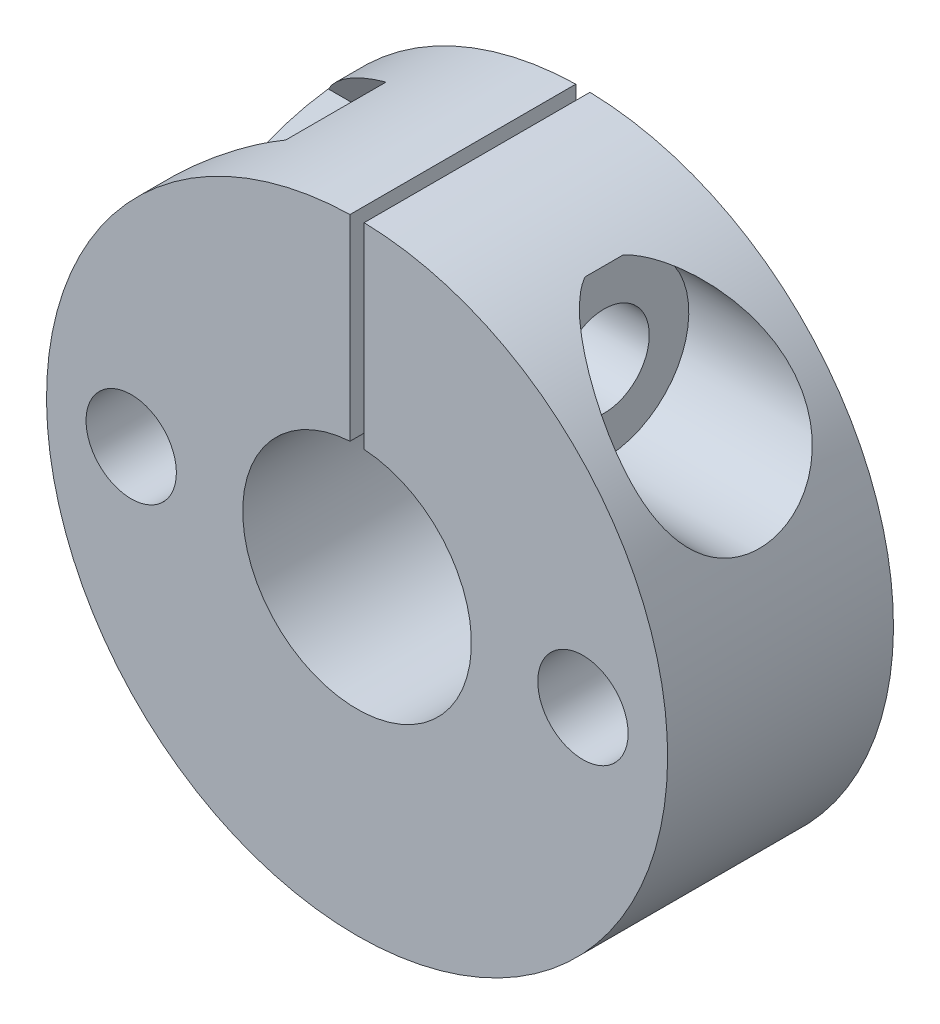
SolidWorks part; units mm, degrees
ref_plane "Front Plane" through (0, 0, 0) normal (0, 0, 1) x (1, 0, 0)
ref_plane "Top Plane" through (0, 0, 0) normal (0, 1, 0) x (1, 0, 0)
ref_plane "Right Plane" through (0, 0, 0) normal (1, 0, 0) x (0, 0, -1)
sketch "ｽｹｯﾁ1" plane through (0, 0, 0) normal (0, 0, 1) x (1, 0, 0)
  line L5 (0.25, -0.9961) -> (-0.25, -0.9961)
  line L6 (0.25, -0.9961) -> (0.25, 12.7013)
  line L7 (0.25, 12.7013) -> (-0.25, 12.7013)
  line L8 (-0.25, -0.9961) -> (-0.25, 12.7013)
  line L9 (0.25, -0.9961) -> (-0.25, 12.7013) construction
  line L10 (0.25, 12.7013) -> (-0.25, -0.9961) construction
  circle A0 centre (0, 0) radius 11
  circle A1 centre (0, 0) radius 4.05
  circle A2 centre (-8, 0) radius 1.6
  circle A3 centre (8, 0) radius 1.6
  point P4 (0, 5.8526)
  dimension "D1" = 8.1
  dimension "D2" = 22
  dimension "D5" = 3.2
  dimension "D6" = 3.2
  dimension "D7" = 8
  dimension "D8" = 8
  dimension "D3" = 0.5
  dimension "D4" = 0.25
extrude "ﾎﾞｽ - 押し出し1" add sketch "ｽｹｯﾁ1" along normal blind 8 contours A1 L8 A0 L6 A3 A2
ref_plane "平面1" through (14.75, 0, 0) normal (1, 0, 0) x (0, 0, -1)
sketch "ｽｹｯﾁ2" plane through (14.75, 0, 0) normal (1, 0, 0) x (0, 0, -1)
  line L0 (-8, 10.9972) -> (-8, -11) construction
  circle A1 centre (-4, 7) radius 3
  dimension "D1" = 6
  dimension "D2" = 4
  dimension "D3" = 7
extrude "ｶｯﾄ - 押し出し1" cut sketch "ｽｹｯﾁ2" against normal blind 10
mirror "ﾐﾗｰ1" about plane through (0, 0, 0) normal (1, 0, 0) of "ｶｯﾄ - 押し出し1"
sketch "ｽｹｯﾁ3" plane through (4.75, 0, 0) normal (1, 0, 0) x (0, 0, -1)
  circle A0 centre (-4, 7) radius 1.6
  dimension "D1" = 3.2
extrude "ｶｯﾄ - 押し出し2" cut sketch "ｽｹｯﾁ3" against normal through all
sketch "ｽｹｯﾁ4" plane through (-4.75, 0, 0) normal (-1, 0, 0) x (0, 0, 1)
  line L1 (7.4641, 7) -> (5.7321, 10)
  line L2 (5.7321, 10) -> (2.2679, 10)
  line L3 (2.2679, 10) -> (0.5359, 7)
  line L4 (0.5359, 7) -> (2.2679, 4)
  line L5 (2.2679, 4) -> (5.7321, 4)
  line L6 (5.7321, 4) -> (7.4641, 7)
  circle A0 centre (4, 7) radius 3 construction
  dimension "D1" = 6
extrude "ｶｯﾄ - 押し出し3" cut sketch "ｽｹｯﾁ4" along normal blind 10
